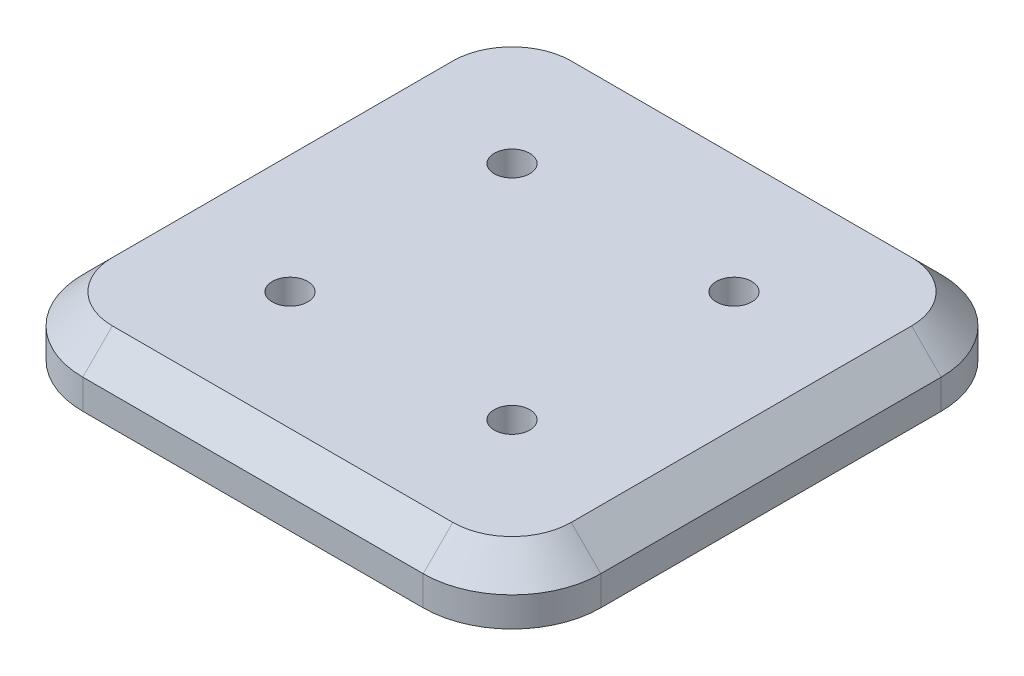
SolidWorks part; units mm, degrees
ref_plane "前基準面" through (0, 0, 0) normal (0, 0, 1) x (1, 0, 0)
ref_plane "上基準面" through (0, 0, 0) normal (0, 1, 0) x (1, 0, 0)
ref_plane "右基準面" through (0, 0, 0) normal (1, 0, 0) x (0, 0, -1)
sketch "草圖1" plane through (0, 0, 0) normal (0, 1, 0) x (1, 0, 0)
  line L1 (0, 0) -> (175, 0)
  line L2 (0, 0) -> (0, 175)
  line L3 (0, 175) -> (175, 175)
  line L4 (175, 0) -> (175, 175)
  dimension "D1" = 175
  dimension "D2" = 175
extrude "填料-伸長1" add sketch "草圖1" along normal blind 20
fillet "圓角1" radius 30 4 edges at (0, 10, -175) (175, 10, -175) (175, 10, 0) (0, 10, 0)
chamfer "導角1" distance 10 angle 45 8 edges at (0, 20, -87.5) (8.7868, 20, -8.7868) (8.7868, 20, -166.2132) (87.5, 20, 0) (87.5, 20, -175) (166.2132, 20, -8.7868) (166.2132, 20, -166.2132) (175, 20, -87.5)
sketch "草圖2" plane through (0, 0, 0) normal (0, -1, 0) x (1, 0, 0)
  line L0 (30, 0) -> (145, 0) construction
  line L1 (25, -25) -> (150, -25)
  line L2 (25, -25) -> (25, -150)
  line L3 (25, -150) -> (150, -150)
  line L4 (150, -25) -> (150, -150)
  line L5 (145, -175) -> (30, -175) construction
  line L6 (175, -30) -> (175, -145) construction
  line L7 (0, -145) -> (0, -30) construction
  dimension "D1" = 25
  dimension "D2" = 25
  dimension "D3" = 25
  dimension "D4" = 25
sketch "草圖4" plane through (0, 20, 0) normal (0, 1, 0) x (1, 0, 0)
  line L0 (25, 25) -> (25, 150) construction
  line L1 (50, 50) -> (125, 50)
  line L2 (50, 50) -> (50, 125)
  line L3 (50, 125) -> (125, 125)
  line L4 (125, 50) -> (125, 125)
  line L5 (25, 25) -> (150, 25) construction
  line L6 (150, 25) -> (150, 150) construction
  line L7 (25, 150) -> (150, 150) construction
  dimension "D1" = 25
  dimension "D2" = 25
  dimension "D3" = 25
  dimension "D4" = 25
hole_wizard "Ø20.0mm 定位孔1" positions "3D草圖2" profile "草圖6" hole size "Ø20.0" standard "ISO"
sketch3d "3D草圖2"
  point P0 (50, 20, -50)
  point P3 (50, 20, -125)
  point P6 (125, 20, -125)
  point P9 (125, 20, -50)
  point P12 (25, 0, -25)
  point P15 (150, 0, -25)
  point P18 (150, 0, -150)
  point P25 (25, 0, -150)
sketch "草圖6" plane through (50, 20, -50) normal (1, 0, 0) x (0, 0, 1)
  line L0 (0, 0) -> (0, 13.6052)
  line L1 (0, 13.6052) -> (6, 10)
  line L2 (6, 10) -> (6, 0)
  line L5 (6, 0) -> (0, 0)
  line L10 (0, 13.6052) -> (-6, 10) construction
  line L11 (0, -6.35) -> (0, 107.95) construction
  dimension "鑽孔直徑" = 12
  dimension "鑽孔深度" = 10
  dimension "導頭角度" = 118
